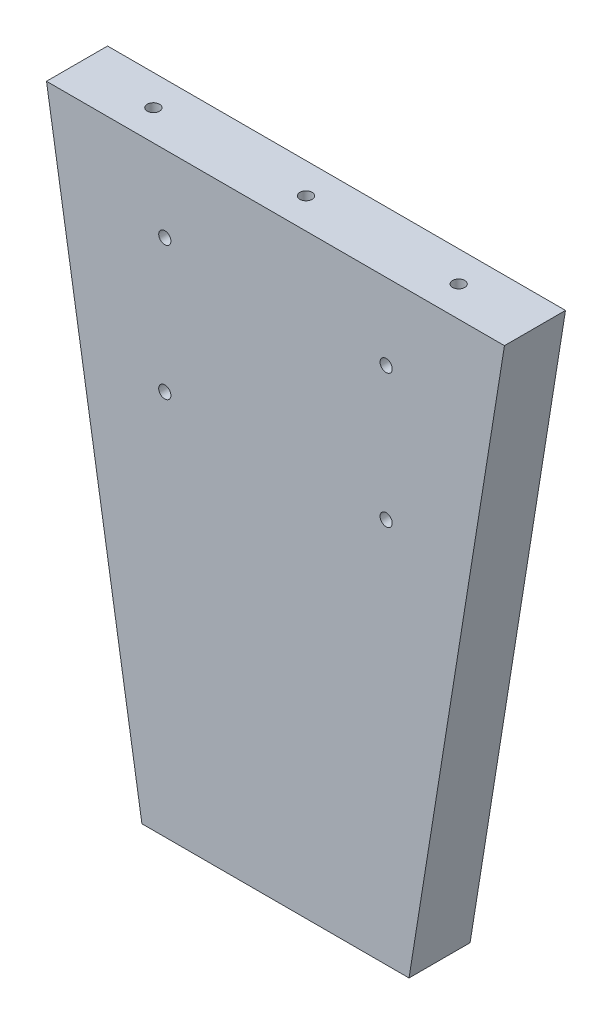
SolidWorks part; units mm, degrees
ref_plane "Płaszczyzna przednia" through (0, 0, 0) normal (0, 0, 1) x (1, 0, 0)
ref_plane "Płaszczyzna górna" through (0, 0, 0) normal (0, 1, 0) x (1, 0, 0)
ref_plane "Płaszczyzna prawa" through (0, 0, 0) normal (1, 0, 0) x (0, 0, -1)
sketch "Szkic1" plane through (0, 0, 0) normal (0, 0, 1) x (1, 0, 0)
  line L0 (35, 0) -> (0, 0)
  line L1 (35, 0) -> (60, 156)
  line L2 (0, 0) -> (0, 156)
  line L3 (0, 156) -> (60, 156)
  dimension "D1" = 156
  dimension "D2" = 35
  dimension "D3" = 60
extrude "Dodanie-wyciągnięcie1" add sketch "Szkic1" along normal mid plane 16 contours L2 L3 L1 L0
mirror "Lustro1" about plane through (0, 0, 8) normal (1, 0, 0) of "Dodanie-wyciągnięcie1"
hole_wizard "Pogłębienie stożkowe pod M3 wkręt do części metalowych z łbem płaskim1" positions "Szkic4" profile "Szkic5" countersink size "M3" standard "Ansi Metric"
sketch "Szkic4" plane through (-255, 156, -8) normal (0, 0, -1) x (-1, 0, 0)
  line L1 (-292, -80) -> (-276, -80) construction
  point P0 (-284, -55)
  point P3 (-284, -20)
sketch "Szkic5" plane through (29, 101, -8) normal (1, 0, 0) x (0, 1, 0)
  line L0 (0, 0) -> (0, 40.9614)
  line L1 (0, 40.9614) -> (1.6, 40)
  line L2 (1.6, 40) -> (1.6, 1.55)
  line L3 (1.6, 1.55) -> (3.15, 0)
  line L4 (3.15, 0) -> (0, 0)
  line L5 (-1.6, 1.55) -> (-3.15, 0) construction
  line L6 (0, 40.9614) -> (-1.6, 40) construction
  line L7 (0, -6.35) -> (0, 107.95) construction
  dimension "Średnica otworu" = 3.2
  dimension "Głębokośc otworu" = 40
  dimension "Średnica zewnętrznego pogłębienia stożkowego" = 6.3
  dimension "Kąt zewnętrznego pogłębienia stożkowego" = 90
  dimension "Kąt wiertła" = 118
pattern_linear "Szyk liniowy2" count 2 spacing 58 along (-1, 0, 0) of "Pogłębienie stożkowe pod M3 wkręt do części metalowych z łbem płaskim1"
hole_wizard "Pogłębienie stożkowe pod M3 wkręt do części metalowych z łbem płaskim2" positions "Szkic6" profile "Szkic7" countersink size "M3" standard "Ansi Metric"
sketch "Szkic6" plane through (-255, 172, 61) normal (0, 1, 0) x (1, 0, 0)
  line L1 (315, 53) -> (315, 69) construction
  line L3 (292, 13) -> (276, 13) construction
  line L5 (234, 13) -> (218, 13) construction
  line L7 (315, 69) -> (195, 69) construction
  point P0 (295, 61)
  point P11 (284, 28)
  point P13 (226, 28)
  point P15 (226, 48)
  point P17 (255, 61)
  point P19 (215, 61)
  point P21 (284, 48)
sketch "Szkic7" plane through (40, 172, 0) normal (1, 0, 0) x (0, 0, 1)
  line L0 (0, 0) -> (0, 40.9614)
  line L1 (0, 40.9614) -> (1.6, 40)
  line L2 (1.6, 40) -> (1.6, 1.55)
  line L3 (1.6, 1.55) -> (3.15, 0)
  line L4 (3.15, 0) -> (0, 0)
  line L5 (-1.6, 1.55) -> (-3.15, 0) construction
  line L6 (0, 40.9614) -> (-1.6, 40) construction
  line L7 (0, -6.35) -> (0, 107.95) construction
  dimension "Średnica otworu" = 3.2
  dimension "Głębokośc otworu" = 40
  dimension "Średnica zewnętrznego pogłębienia stożkowego" = 6.3
  dimension "Kąt zewnętrznego pogłębienia stożkowego" = 90
  dimension "Kąt wiertła" = 118
